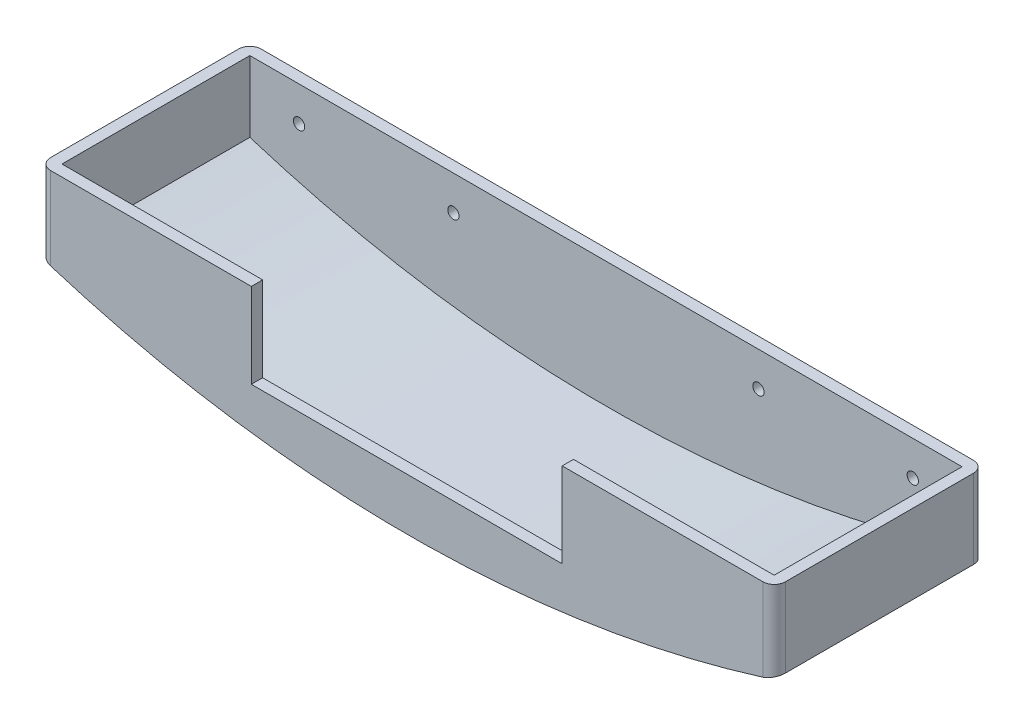
SolidWorks part; units mm, degrees
ref_plane "Front Plane" through (0, 0, 0) normal (0, 0, 1) x (1, 0, 0)
ref_plane "Top Plane" through (0, 0, 0) normal (0, 1, 0) x (1, 0, 0)
ref_plane "Right Plane" through (0, 0, 0) normal (1, 0, 0) x (0, 0, -1)
sketch "Sketch1" plane through (0, 0, 0) normal (0, 0, 1) x (1, 0, 0)
  line L0 (65, 0) -> (-65, 0)
  line L1 (65, 0) -> (65, -14)
  line L2 (-65, 0) -> (-65, -14)
  arc A1 (65, -14) -> (-65, -14) centre (0, 187.7895) cw
  point P1 (0, -24.2105)
  dimension "D1" = 130
  dimension "D3" = 212
  dimension "D2" = 14
extrude "Boss-Extrude1" add sketch "Sketch1" against normal blind 37.24
shell "Shell1" thickness 2
sketch "Sketch2" plane through (0, 0, 0) normal (0, 0, 1) x (1, 0, 0)
  line L0 (-27.5, 0) -> (-27.5, -15)
  line L1 (65, 0) -> (-65, 0) construction
  line L2 (-27.5, -15) -> (27.5, -15)
  line L3 (27.5, -15) -> (27.5, 0)
  line L4 (27.5, 0) -> (-27.5, 0)
  point P4 (0, -15)
  dimension "D1" = 55
  dimension "D2" = 15
extrude "Cut-Extrude1" cut sketch "Sketch2" against normal blind 10
sketch "Sketch3" plane through (0, 0, -37.24) normal (0, 0, -1) x (-1, 0, 0)
  line L0 (0, 0) -> (0, -24.2105) construction
  circle A0 centre (-54.2856, -6.1) radius 1
  circle A1 centre (-26.9856, -6.1) radius 1
  circle A2 centre (54.2856, -6.1) radius 1
  circle A3 centre (26.9856, -6.1) radius 1
  arc A5 (-65, -14) -> (65, -14) centre (0, 187.7895) ccw construction
  point P12 (0, 0)
  point P16 (0, -24.2105)
  dimension "D1" = 2
  dimension "D2" = 2
extrude "Cut-Extrude2" cut sketch "Sketch3" against normal blind 12
fillet "Fillet1" radius 2 4 edges at (-65, -7, -37.24) (-65, -7, 0) (65, -7, -37.24) (65, -7, 0)
